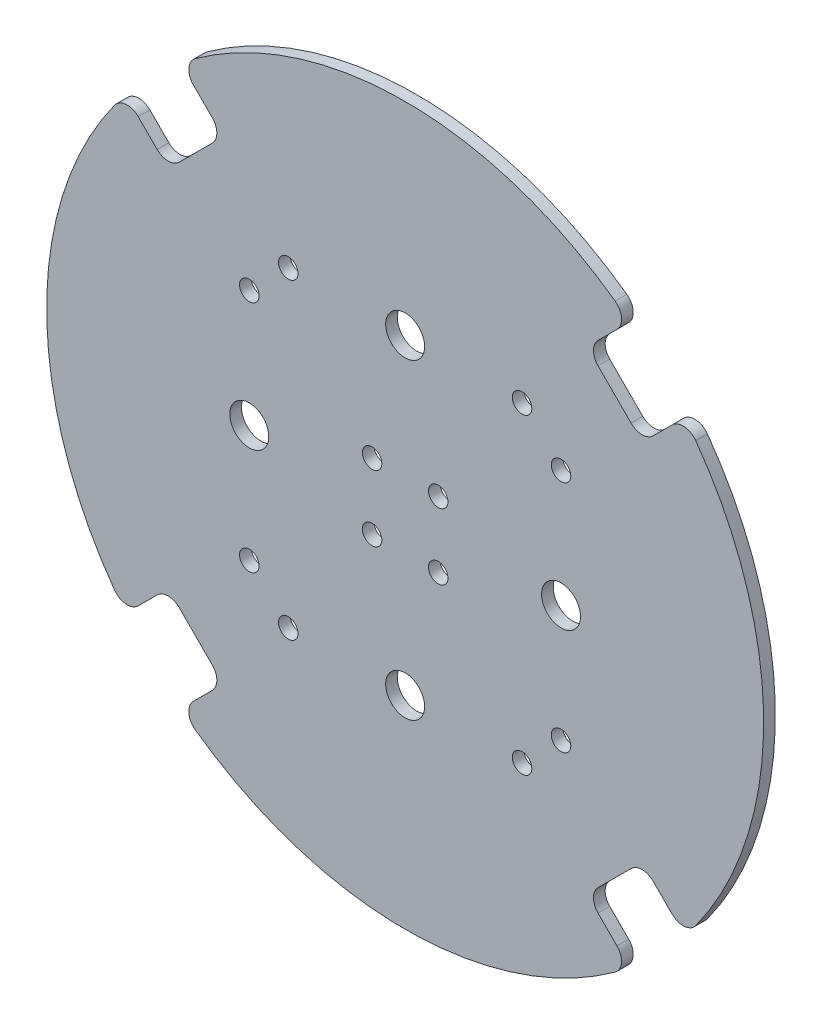
SolidWorks part; units mm, degrees
ref_plane "Front Plane" through (0, 0, 0) normal (0, 0, 1) x (1, 0, 0)
ref_plane "Top Plane" through (0, 0, 0) normal (0, 1, 0) x (1, 0, 0)
ref_plane "Right Plane" through (0, 0, 0) normal (1, 0, 0) x (0, 0, -1)
sketch "Sketch4" plane through (0, 0, 0) normal (0, 0, 1) x (1, 0, 0)
  line L0 (20, 0) -> (20, 16.1509) construction
  line L1 (0, 20) -> (-19.1479, 20) construction
  line L2 (-20, 0) -> (-20, 17.3971) construction
  line L3 (0, -20) -> (22.3917, -20) construction
  line L4 (0, 20) -> (-20.9516, 40.9516)
  line L5 (0, 20) -> (20.9516, 40.9516)
  line L6 (0, 0) -> (0, 59.0315) construction
  line L7 (0, 0) -> (60.9979, 0) construction
  line L8 (20, 0) -> (40.9516, 20.9516)
  line L9 (20, 0) -> (40.9516, -20.9516)
  line L10 (-20, 0) -> (-40.9516, 20.9516)
  line L11 (-20, 0) -> (-40.9516, -20.9516)
  line L12 (0, -20) -> (-20.9516, -40.9516)
  line L13 (0, -20) -> (20.9516, -40.9516)
  line L14 (-35.8697, 28.7987) -> (-30.4056, 23.3345)
  line L15 (-30.4056, 23.3345) -> (-23.3345, 30.4056)
  line L16 (-23.3345, 30.4056) -> (-28.7987, 35.8697)
  line L17 (0, 0) -> (-47.992, 47.992) construction
  line L18 (0, 0) -> (52.7868, 52.7868) construction
  line L19 (28.7987, 35.8697) -> (23.3345, 30.4056)
  line L20 (23.3345, 30.4056) -> (30.4056, 23.3345)
  line L21 (30.4056, 23.3345) -> (35.8697, 28.7987)
  line L22 (28.7987, -35.8697) -> (23.3345, -30.4056)
  line L23 (23.3345, -30.4056) -> (30.4056, -23.3345)
  line L24 (30.4056, -23.3345) -> (35.8697, -28.7987)
  line L25 (-35.8697, -28.7987) -> (-30.4056, -23.3345)
  line L26 (-30.4056, -23.3345) -> (-23.3345, -30.4056)
  line L27 (-23.3345, -30.4056) -> (-28.7987, -35.8697)
  circle A0 centre (0, 20) radius 14
  circle A1 centre (20, 0) radius 14
  circle A2 centre (0, -20) radius 14
  circle A3 centre (-20, 0) radius 14
  circle A4 centre (-15, 20) radius 1.25
  circle A5 centre (15, 20) radius 1.25
  circle A6 centre (20, 15) radius 1.25
  circle A7 centre (20, -15) radius 1.25
  circle A8 centre (15, -20) radius 1.25
  circle A9 centre (-15, -20) radius 1.25
  circle A10 centre (-20, 15) radius 1.25
  circle A11 centre (-20, -15) radius 1.25
  circle A12 centre (0, 0) radius 46
  circle A13 centre (0, 20) radius 2.5
  circle A14 centre (-20, 0) radius 2.5
  circle A15 centre (20, 0) radius 2.5
  circle A16 centre (0, -20) radius 2.5
  circle A17 centre (4.2426, 4.2426) radius 1.25
  circle A18 centre (-4.2426, -4.2426) radius 1.25
  circle A19 centre (-4.2426, 4.2426) radius 1.25
  circle A20 centre (4.2426, -4.2426) radius 1.25
  point P39 (0, 46)
  point P63 (-26.8701, 26.8701)
  point P65 (-32.5269, 32.5269)
  point P67 (26.8701, 26.8701)
  point P71 (32.5269, 32.5269)
  point P79 (26.8701, -26.8701)
  point P81 (32.5269, -32.5269)
  point P82 (-32.5269, -32.5269)
  point P85 (-26.8701, -26.8701)
  dimension "D1" = 28
  dimension "D2" = 28
  dimension "D3" = 28
  dimension "D4" = 28
  dimension "D5" = 2.5
  dimension "D6" = 2.5
  dimension "D7" = 2.5
  dimension "D8" = 2.5
  dimension "D9" = 2.5
  dimension "D10" = 2.5
  dimension "D11" = 2.5
  dimension "D12" = 2.5
  dimension "D17" = 15
  dimension "D26" = 5
  dimension "D27" = 5
  dimension "D28" = 5
  dimension "D29" = 5
  dimension "D40" = 2.5
  dimension "D41" = 2.5
  dimension "D44" = 2.5
  dimension "D45" = 2.5
  dimension "D13" = 15
  dimension "D14" = 15
  dimension "D15" = 15
  dimension "D16" = 15
  dimension "D18" = 15
  dimension "D19" = 15
  dimension "D20" = 15
  dimension "D21" = 26
  dimension "D22" = 45
  dimension "D23" = 45
  dimension "D24" = 45
  dimension "D25" = 45
  dimension "D30" = 45
  dimension "D31" = 45
  dimension "D32" = 10
  dimension "D33" = 8
  dimension "D34" = 10
  dimension "D35" = 8
  dimension "D36" = 10
  dimension "D37" = 8
  dimension "D38" = 8
  dimension "D39" = 10
  dimension "D42" = 6
  dimension "D43" = 6
  dimension "D46" = 6
  dimension "D47" = 6
sketch "Sketch5" plane through (0, 0, 0) normal (0, 0, 1) x (1, 0, 0)
  line L0 (-34.252, 27.1809) -> (-31.8198, 24.7487)
  line L1 (-28.9914, 24.7487) -> (-24.7487, 28.9914)
  line L2 (-24.7487, 31.8198) -> (-27.1809, 34.252)
  line L3 (27.1809, 34.252) -> (24.7487, 31.8198)
  line L4 (24.7487, 28.9914) -> (28.9914, 24.7487)
  line L5 (31.8198, 24.7487) -> (34.252, 27.1809)
  line L6 (-34.252, -27.1809) -> (-31.8198, -24.7487)
  line L7 (-28.9914, -24.7487) -> (-24.7487, -28.9914)
  line L8 (-24.7487, -31.8198) -> (-27.1809, -34.252)
  line L9 (27.1809, -34.252) -> (24.7487, -31.8198)
  line L10 (24.7487, -28.9914) -> (28.9914, -24.7487)
  line L11 (31.8198, -24.7487) -> (34.252, -27.1809)
  circle A0 centre (-20, 0) radius 2.5
  circle A1 centre (-20, 15) radius 1.25
  circle A2 centre (-20, -15) radius 1.25
  circle A3 centre (-15, -20) radius 1.25
  circle A4 centre (0, -20) radius 2.5
  circle A5 centre (15, -20) radius 1.25
  circle A6 centre (20, -15) radius 1.25
  circle A7 centre (20, 0) radius 2.5
  circle A8 centre (20, 15) radius 1.25
  circle A9 centre (15, 20) radius 1.25
  circle A10 centre (0, 20) radius 2.5
  circle A11 centre (-15, 20) radius 1.25
  circle A12 centre (-15, 20) radius 1.25 construction
  circle A13 centre (0, 20) radius 2.5 construction
  circle A14 centre (15, 20) radius 1.25 construction
  circle A15 centre (-20, 15) radius 1.25 construction
  circle A16 centre (-20, 0) radius 2.5 construction
  circle A17 centre (20, 15) radius 1.25 construction
  circle A18 centre (20, 0) radius 2.5 construction
  circle A19 centre (20, -15) radius 1.25 construction
  circle A20 centre (15, -20) radius 1.25 construction
  circle A21 centre (0, -20) radius 2.5 construction
  circle A22 centre (-15, -20) radius 1.25 construction
  circle A23 centre (-20, -15) radius 1.25 construction
  arc A24 (37.2874, 26.9379) -> (37.2874, -26.9379) centre (0, 0) cw
  arc A25 (26.9379, 37.2874) -> (-26.9379, 37.2874) centre (0, 0) ccw
  arc A26 (-37.2874, 26.9379) -> (-37.2874, -26.9379) centre (0, 0) ccw
  arc A27 (26.9379, -37.2874) -> (-26.9379, -37.2874) centre (0, 0) cw
  arc A28 (-37.2874, -26.9379) -> (-34.252, -27.1809) centre (-35.6662, -25.7667) ccw
  arc A29 (-31.8198, -24.7487) -> (-28.9914, -24.7487) centre (-30.4056, -26.163) cw
  arc A30 (-24.7487, -28.9914) -> (-24.7487, -31.8198) centre (-26.163, -30.4056) cw
  arc A31 (-27.1809, -34.252) -> (-26.9379, -37.2874) centre (-25.7667, -35.6662) ccw
  arc A32 (27.1809, -34.252) -> (26.9379, -37.2874) centre (25.7667, -35.6662) cw
  arc A33 (24.7487, -28.9914) -> (24.7487, -31.8198) centre (26.163, -30.4056) ccw
  arc A34 (28.9914, -24.7487) -> (31.8198, -24.7487) centre (30.4056, -26.163) cw
  arc A35 (34.252, -27.1809) -> (37.2874, -26.9379) centre (35.6662, -25.7667) ccw
  arc A36 (37.2874, 26.9379) -> (34.252, 27.1809) centre (35.6662, 25.7667) ccw
  arc A37 (31.8198, 24.7487) -> (28.9914, 24.7487) centre (30.4056, 26.163) cw
  arc A38 (24.7487, 31.8198) -> (24.7487, 28.9914) centre (26.163, 30.4056) ccw
  arc A39 (26.9379, 37.2874) -> (27.1809, 34.252) centre (25.7667, 35.6662) cw
  arc A40 (-26.9379, 37.2874) -> (-27.1809, 34.252) centre (-25.7667, 35.6662) ccw
  arc A41 (-37.2874, 26.9379) -> (-34.252, 27.1809) centre (-35.6662, 25.7667) cw
  arc A42 (-24.7487, 31.8198) -> (-24.7487, 28.9914) centre (-26.163, 30.4056) cw
  arc A43 (-28.9914, 24.7487) -> (-31.8198, 24.7487) centre (-30.4056, 26.163) cw
  circle A44 centre (4.2426, 4.2426) radius 1.25
  circle A45 centre (-4.2426, 4.2426) radius 1.25
  circle A46 centre (-4.2426, -4.2426) radius 1.25
  circle A47 centre (4.2426, -4.2426) radius 1.25
  circle A48 centre (4.2426, 4.2426) radius 1.25 construction
  circle A49 centre (-4.2426, 4.2426) radius 1.25 construction
  circle A50 centre (4.2426, -4.2426) radius 1.25 construction
  circle A51 centre (-4.2426, -4.2426) radius 1.25 construction
  point P97 (-35.8697, -28.7987)
  point P100 (-30.4056, -23.3345)
  point P103 (-23.3345, -30.4056)
  point P106 (-28.7987, -35.8697)
  point P109 (28.7987, -35.8697)
  point P112 (23.3345, -30.4056)
  point P115 (30.4056, -23.3345)
  point P118 (35.8697, -28.7987)
  point P121 (35.8697, 28.7987)
  point P124 (30.4056, 23.3345)
  point P127 (23.3345, 30.4056)
  point P130 (28.7987, 35.8697)
  point P133 (-28.7987, 35.8697)
  point P136 (-35.8697, 28.7987)
  point P139 (-23.3345, 30.4056)
  point P142 (-30.4056, 23.3345)
  dimension "D1" = 2
extrude "Boss-Extrude1" add sketch "Sketch5" along normal blind 1.5
